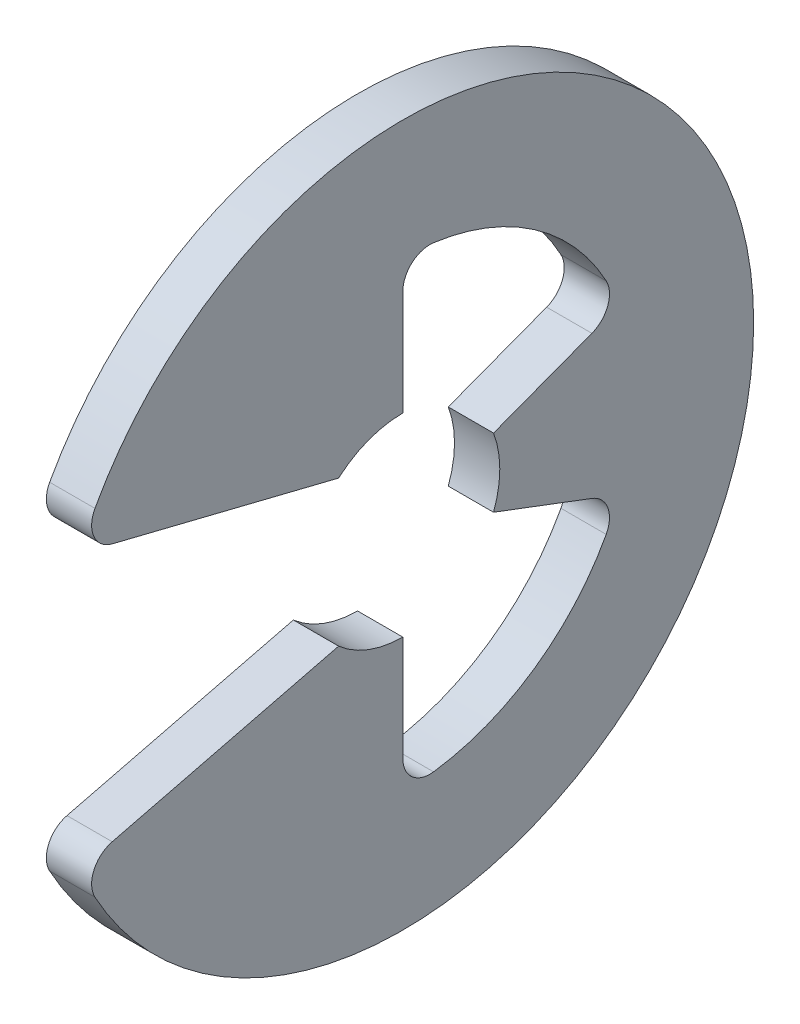
SolidWorks part; units mm, degrees
ref_plane "Front" through (0, 0, 0) normal (0, 0, 1) x (1, 0, 0)
ref_plane "Top" through (0, 0, 0) normal (0, 1, 0) x (1, 0, 0)
ref_plane "Right" through (0, 0, 0) normal (1, 0, 0) x (0, 0, -1)
sketch "Sketch1" plane through (0, 0, 0) normal (1, 0, 0) x (0, 0, -1)
  line L0 (-4.9942, -2.1186) -> (-0.9922, -1.125)
  line L1 (-4.9942, 2.1186) -> (-0.9922, 1.125)
  line L2 (0, -1.5) -> (0, -3.5742)
  line L3 (0, 1.5) -> (0, 3.5742)
  line L4 (1.4031, -0.5303) -> (3.3434, -1.2637)
  line L5 (1.4031, 0.5303) -> (3.3434, 1.2637)
  line L6 (0, 0) -> (-3, 0) construction
  line L7 (1.4031, 0.5303) -> (1.4031, -0.5303) construction
  line L8 (0, -1.5) -> (-0.9922, -1.125) construction
  circle A1 centre (0, 0) radius 3 construction
  circle A2 centre (0, 0) radius 1.5 construction
  arc A3 (-4.9942, -2.1186) -> (-4.9942, 2.1186) centre (0, 0) ccw
  arc A4 (-0.9922, -1.125) -> (0, -1.5) centre (0, 0) ccw
  arc A5 (-0.9922, 1.125) -> (0, 1.5) centre (0, 0) cw
  arc A6 (1.4031, 0.5303) -> (1.4031, -0.5303) centre (0, 0) cw
  arc A7 (0, -3.5742) -> (3.3434, -1.2637) centre (0, 0) ccw
  arc A8 (3.3434, 1.2637) -> (0, 3.5742) centre (0, 0) ccw
  dimension "D" = 3
  dimension "D1" = 3.5742
  dimension "OD" = 10.85
  dimension "D2" = 1.7056
  dimension "D3" = 2.25
extrude "Extrude1" add sketch "Sketch1" along normal mid plane 0.7
fillet "Fillet1" radius 0.42 6 edges at (0, -3.5742, 0) (0, 3.5742, 0) (0, -2.1186, 4.9942) (0, 2.1186, 4.9942) (0, -1.2637, -3.3434) (0, 1.2637, -3.3434)
sketch "Sketch3" plane through (0, 0, 0) normal (0, 1, 0) x (1, 0, 0)
  line L0 (0.37, 3) -> (0.37, 2.5)
  line L1 (0.37, 2.5) -> (-0.37, 2.5)
  line L2 (-0.37, 2.5) -> (-0.37, 3)
  line L3 (-0.37, 3) -> (-5.18, 3)
  line L4 (2.22, 0) -> (2.22, 2.75)
  line L5 (-5.18, 3) -> (-5.18, 0)
  line L6 (-5.18, 0) -> (2.22, 0)
  line L8 (2.22, 0) -> (2.22, 3) construction
  line L9 (2.22, 3) -> (0.37, 3) construction
  line L10 (2.22, 0) -> (17.2631, 0) construction
  line L11 (2.22, 2.75) -> (1.97, 3)
  line L12 (1.97, 3) -> (0.37, 3)
  point P2 (0, 2.5)
  point P5 (0.37, 2.75)
  dimension "D2" = 7.4
  dimension "D1" = 1.85
  dimension "D3" = 45
revolve "Revolve2" [suppressed] add sketch "Sketch3" angle 360 about L10
equation "\"D2@Sketch3\" = \"W@Sketch3\"*10"
equation "\"D1@Sketch3\" = \"D2@Sketch3\"/4"
equation "\"D1@Sketch1\" = (\"OD@Sketch1\"+\"D@Sketch1\")/3.875"
equation "\"D3@Sketch1\" = \"D@Sketch1\"*.75"
equation "\"D1@Fillet1\" = \"D1@Extrude1\"*.6"
